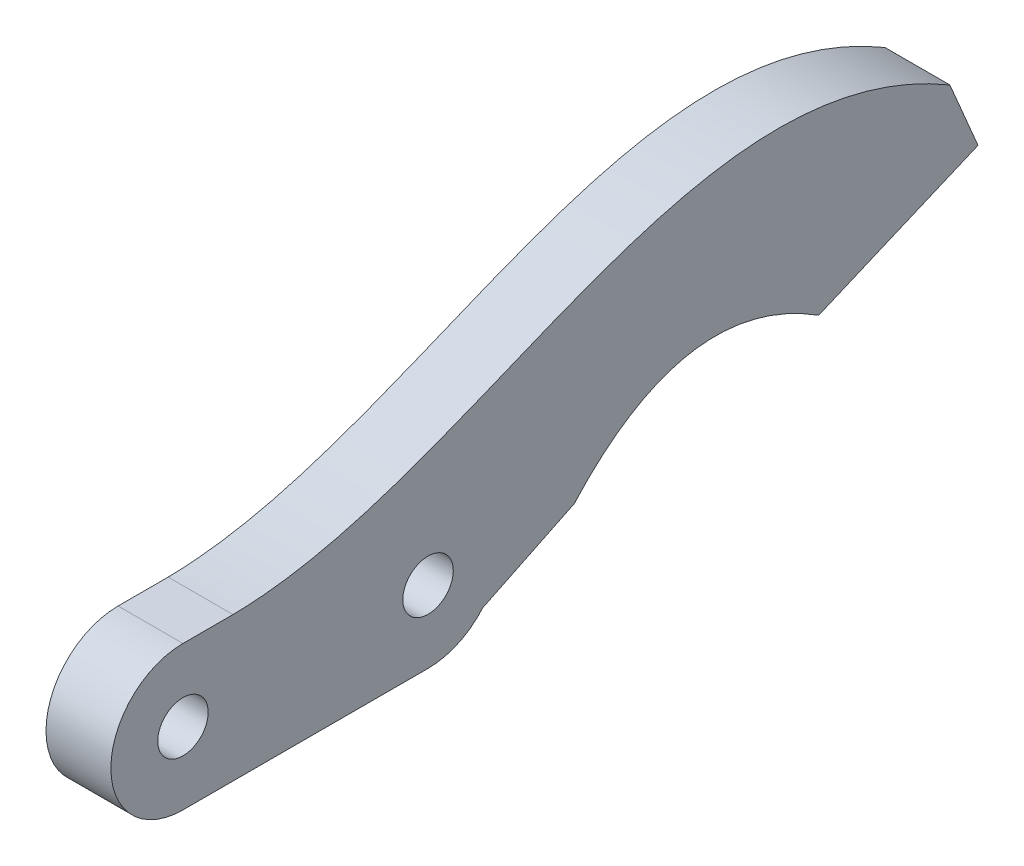
SolidWorks part; units mm, degrees
ref_plane "Front Plane" through (0, 0, 0) normal (0, 0, 1) x (1, 0, 0)
ref_plane "Top Plane" through (0, 0, 0) normal (0, 1, 0) x (1, 0, 0)
ref_plane "Right Plane" through (0, 0, 0) normal (1, 0, 0) x (0, 0, -1)
sketch "Sketch1" plane through (0, 0, 0) normal (1, 0, 0) x (0, 0, -1)
  line L1 (0, 0) -> (27, 0)
  line L2 (0, 0) -> (0, 10)
  line L3 (0, 10) -> (22, 10)
  circle A0 centre (5, 5) radius 1.75
  circle A1 centre (5, 5) radius 5
  circle A2 centre (22, 5) radius 5
  circle A3 centre (22, 5) radius 1.75
  dimension "D7" = 3.5
  dimension "D11" = 10
  dimension "D2" = 3.5
  dimension "D1" = 10
  dimension "D8" = 5
  dimension "D9" = 5
  dimension "D10" = 17
extrude "Boss-Extrude1" add sketch "Sketch1" along normal blind 4.5 contours A1 A0 | A2 L3 A1 L1 | A2 A3 | L2 A1 | L1 A1
sketch "Sketch2" plane through (4.5, 0, 5.9488) normal (1, 0, 0) x (0, 0, -1)
  line L14 (5.0017, 10.1224) -> (26.9995, 9.8127)
  line L20 (28.8247, 0.3277) -> (38.0854, 4.8241)
  line L21 (55.0455, 7.6656) -> (66.0942, 12.3481)
  line L22 (66.0942, 12.3481) -> (64.1432, 16.9517)
  arc A4 (26.5704, -0.1739) -> (26.9995, 9.8127) centre (26.6408, 4.8256) ccw
  spline S0 degree 2 poles (38.0854, 4.8241) (45.8792, 13.4817) (55.0455, 7.6656) knots 0 0 0 1 1 1
  spline S1 degree 3 poles (64.1432, 16.9517) (46.3659, 27.4751) (31.1773, 9.7539) (13.695, 10) knots 0 0 0 0 1 1 1 1
  point P2 (27, 5)
  dimension "D3" = 5
  dimension "D4" = 12
extrude "Boss-Extrude2" add sketch "Sketch2" against normal blind 4.5
